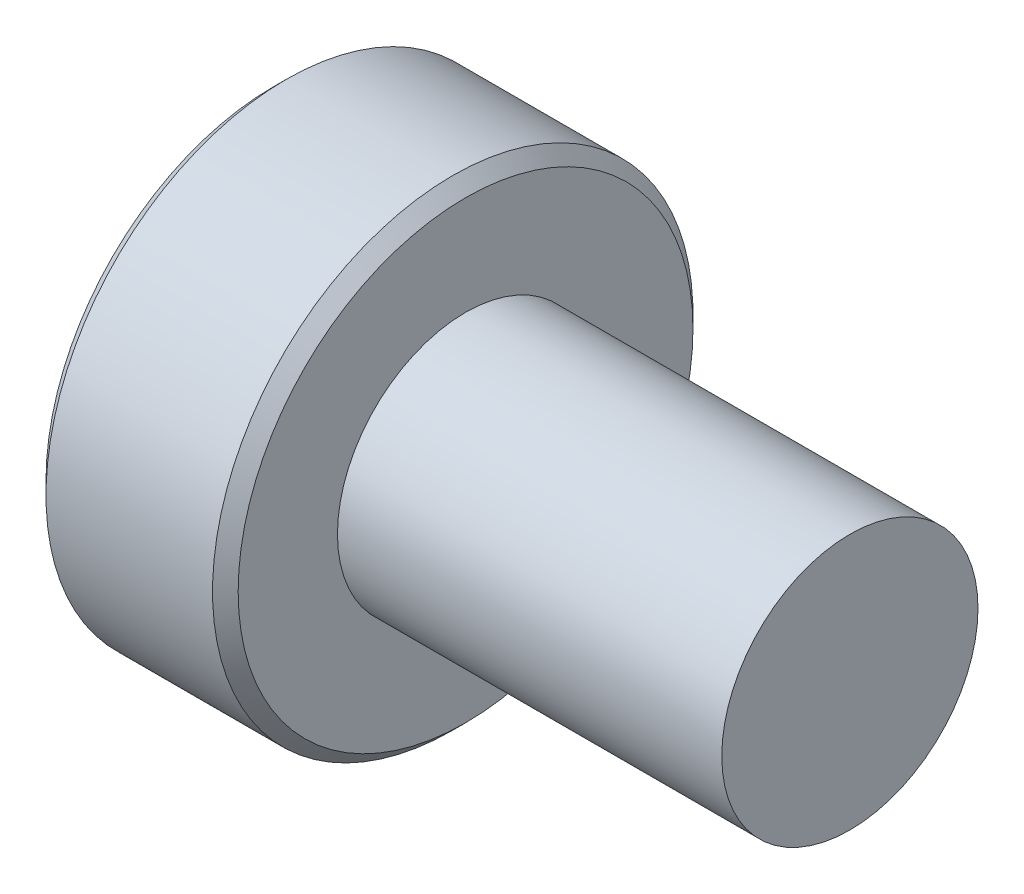
SolidWorks part; units mm, degrees
ref_plane "Front Plane" through (0, 0, 0) normal (0, 0, 1) x (1, 0, 0)
ref_plane "Top Plane" through (0, 0, 0) normal (0, 1, 0) x (1, 0, 0)
ref_plane "Right Plane" through (0, 0, 0) normal (1, 0, 0) x (0, 0, -1)
sketch "Sketch1" plane through (0, 0, 0) normal (0, 0, 1) x (1, 0, 0)
  line L0 (0, 0) -> (0, 3.75)
  line L1 (9, 0) -> (0, 0)
  line L2 (0, 3.75) -> (3, 3.75)
  line L4 (3, 3.75) -> (3, 2)
  line L5 (3, 2) -> (9, 2)
  line L7 (9, 2) -> (9, 0)
  line L9 (9, 0) -> (0, 0) construction
  dimension "KN_M" = 4
  dimension "KN_T" = 3
  dimension "KN_D" = 7.5
  dimension "KN_L" = 6
revolve "Revolve1" add sketch "Sketch1" angle 360 about L9
cosmetic thread "Cosmetic Thread1" parameters "KN_TD_s"=3.22
chamfer "Chamfer1" distance 0.2 angle 45 2 edges at (0, -3.75, 0) (3, -3.75, 0)
